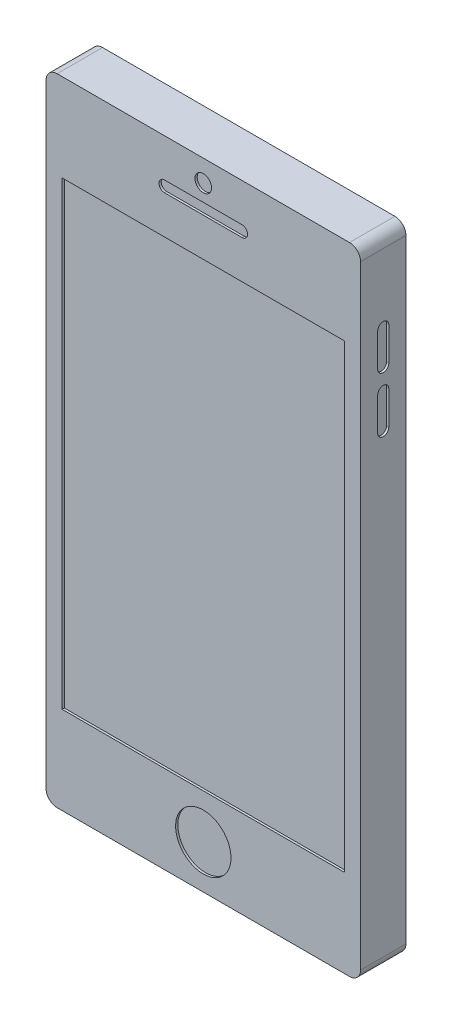
SolidWorks part; units mm, degrees
ref_plane "Front Plane" through (0, 0, 0) normal (0, 0, 1) x (1, 0, 0)
ref_plane "Top Plane" through (0, 0, 0) normal (0, 1, 0) x (1, 0, 0)
ref_plane "Right Plane" through (0, 0, 0) normal (1, 0, 0) x (0, 0, -1)
sketch "Sketch1" plane through (0, 0, 0) normal (0, 0, 1) x (1, 0, 0)
  line L1 (-36.068, 72.898) -> (36.068, 72.898)
  line L2 (-36.068, 72.898) -> (-36.068, -72.898)
  line L3 (-36.068, -72.898) -> (36.068, -72.898)
  line L4 (36.068, 72.898) -> (36.068, -72.898)
  line L5 (-36.068, 72.898) -> (36.068, -72.898) construction
  line L6 (-36.068, -72.898) -> (36.068, 72.898) construction
  point P0 (0, 0)
  dimension "D1" = 145.796
  dimension "D2" = 72.136
extrude "Boss-Extrude1" add sketch "Sketch1" along normal mid plane 10.414
fillet "Fillet1" radius 2.54 4 edges at (-36.068, -72.898, 0) (36.068, -72.898, 0) (-36.068, 72.898, 0) (36.068, 72.898, 0)
sketch "Sketch2" plane through (0, 0, 5.207) normal (0, 0, 1) x (1, 0, 0)
  line L0 (0, -52.7828) -> (0, -62.9428) construction
  line L1 (-32.385, -52.7828) -> (32.385, -52.7828)
  line L2 (-32.385, -52.7828) -> (-32.385, 52.7828)
  line L3 (-32.385, 52.7828) -> (32.385, 52.7828)
  line L4 (32.385, -52.7828) -> (32.385, 52.7828)
  line L5 (-32.385, -52.7828) -> (32.385, 52.7828) construction
  line L6 (-32.385, 52.7828) -> (32.385, -52.7828) construction
  line L7 (0, 52.7828) -> (0, 72.898) construction
  line L8 (33.528, 72.898) -> (-33.528, 72.898) construction
  line L9 (-8.89, 62.8404) -> (8.89, 62.8404) construction
  line L10 (-8.89, 64.1104) -> (8.89, 64.1104)
  line L11 (-8.89, 61.5704) -> (8.89, 61.5704)
  circle A0 centre (0, -62.9428) radius 6.35
  arc A1 (-8.89, 64.1104) -> (-8.89, 61.5704) centre (-8.89, 62.8404) ccw
  arc A2 (8.89, 61.5704) -> (8.89, 64.1104) centre (8.89, 62.8404) ccw
  circle A3 centre (0, 67.9204) radius 1.905
  point P0 (0, 0)
  point P15 (0, 62.8404)
  dimension "D4" = 12.7
  dimension "D8" = 3.81
  dimension "D1" = 64.77
  dimension "D2" = 105.5656
  dimension "D3" = 10.16
  dimension "D5" = 2.54
  dimension "D6" = 17.78
  dimension "D7" = 5.08
extrude "Cut-Extrude1" cut sketch "Sketch2" against normal blind 0.508
sketch "Sketch4" plane through (0, 0, -5.207) normal (0, 0, -1) x (-1, 0, 0)
  circle A0 centre (25.4, 63.5) radius 3.81
  dimension "D1" = 7.62
  dimension "D2" = 25.4
  dimension "D3" = 63.5
extrude "Cut-Extrude2" cut sketch "Sketch4" against normal blind 0.508
sketch "Sketch5" plane through (36.068, 0, 0) normal (1, 0, 0) x (0, 0, -1)
  line L0 (0, 70.358) -> (0, -70.358) construction
  line L1 (5.207, 70.358) -> (-5.207, 70.358) construction
  line L2 (-5.207, -70.358) -> (5.207, -70.358) construction
  line L3 (0, 54.61) -> (0, 46.99) construction
  line L4 (1.27, 54.61) -> (1.27, 46.99)
  line L5 (-1.27, 54.61) -> (-1.27, 46.99)
  line L6 (0, 41.91) -> (0, 34.29) construction
  line L7 (1.27, 41.91) -> (1.27, 34.29)
  line L8 (-1.27, 41.91) -> (-1.27, 34.29)
  arc A0 (1.27, 54.61) -> (-1.27, 54.61) centre (0, 54.61) ccw
  arc A1 (-1.27, 46.99) -> (1.27, 46.99) centre (0, 46.99) ccw
  arc A2 (1.27, 41.91) -> (-1.27, 41.91) centre (0, 41.91) ccw
  arc A3 (-1.27, 34.29) -> (1.27, 34.29) centre (0, 34.29) ccw
  point P8 (0, 50.8)
  point P13 (0, 38.1)
  dimension "D1" = 2.54
  dimension "D2" = 12.7
  dimension "D3" = 38.1
  dimension "D4" = 7.62
extrude "Cut-Extrude3" cut sketch "Sketch5" against normal blind 0.508
